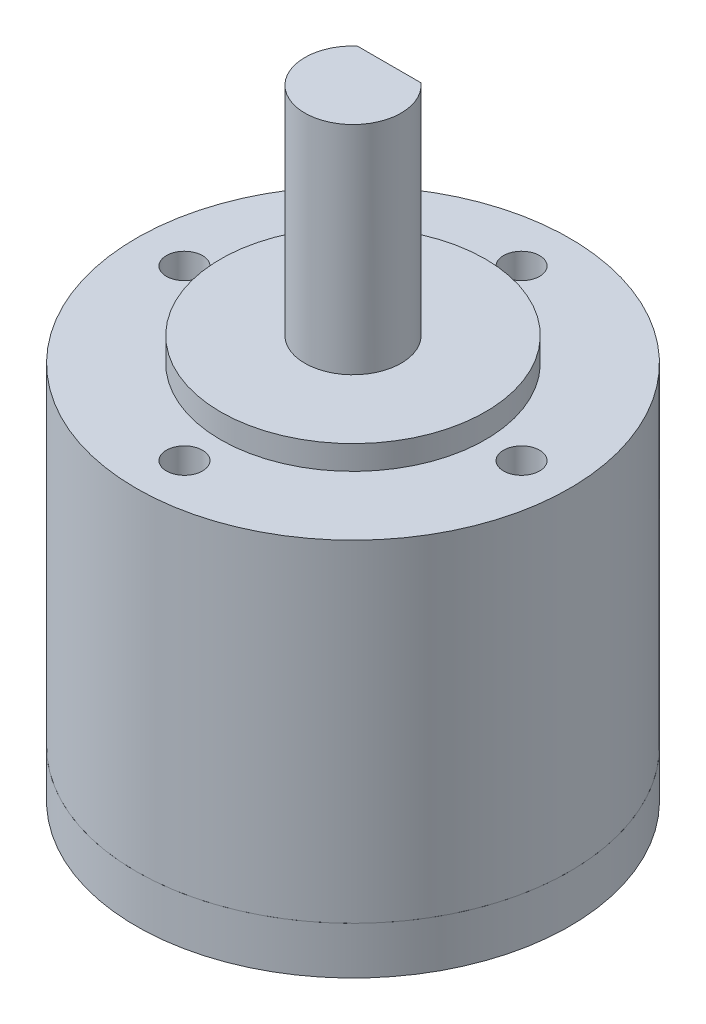
SolidWorks part; units mm, degrees
ref_plane "Front Plane" through (0, 0, 0) normal (0, 0, 1) x (1, 0, 0)
ref_plane "Top Plane" through (0, 0, 0) normal (0, 1, 0) x (1, 0, 0)
ref_plane "Right Plane" through (0, 0, 0) normal (1, 0, 0) x (0, 0, -1)
sketch "Sketch1" plane through (0, 0, 0) normal (0, 1, 0) x (1, 0, 0)
  circle A0 centre (0, 0) radius 18
  dimension "D1" = 36
extrude "Boss-Extrude1" add sketch "Sketch1" along normal mid plane 27.559
sketch "Sketch2" plane through (0, 13.7795, 0) normal (0, 1, 0) x (1, 0, 0)
  circle A0 centre (0, 0) radius 11
  dimension "D1" = 22
extrude "Boss-Extrude2" add sketch "Sketch2" along normal blind 2
sketch "Sketch3" plane through (0, 15.7795, 0) normal (0, 1, 0) x (1, 0, 0)
  circle A0 centre (0, 0) radius 4
  dimension "D1" = 8
extrude "Boss-Extrude4" add sketch "Sketch3" along normal blind 18
sketch "Sketch4" plane through (0, 33.7795, 0) normal (0, 1, 0) x (1, 0, 0)
  line L0 (-2.6458, 3) -> (2.6458, 3)
  line L1 (0, -4) -> (0, 3) construction
  arc A0 (0, -4) -> (2.6458, 3) centre (0, 0) ccw construction
  circle A1 centre (0, 0) radius 4
  arc A2 (2.6458, 3) -> (-2.6458, 3) centre (0, 0) ccw
  arc A3 (-2.6458, 3) -> (0, -4) centre (0, 0) ccw construction
  dimension "D2" = 7
  dimension "D1" = 0
extrude "Cut-Extrude1" cut sketch "Sketch4" against normal blind 15
sketch "Sketch5" plane through (0, 13.7795, 0) normal (0, 1, 0) x (1, 0, 0)
  circle A0 centre (0, 0) radius 14 construction
  circle A1 centre (0, 14) radius 1.5
  circle A2 centre (-14, 0) radius 1.5
  circle A3 centre (0, -14) radius 1.5
  circle A4 centre (14, 0) radius 1.5
  dimension "D1" = 28
  dimension "D2" = 3
extrude "Cut-Extrude2" cut sketch "Sketch5" against normal through all
sketch "Sketch6" plane through (0, -13.7795, 0) normal (0, -1, 0) x (1, 0, 0)
  circle A0 centre (0, 0) radius 11.178
  dimension "D1" = 22.356
extrude "Cut-Extrude3" cut sketch "Sketch6" against normal blind 20
sketch "Sketch7" plane through (0, -13.7795, 0) normal (0, -1, 0) x (1, 0, 0)
  circle A1 centre (0, 0) radius 18
  circle A2 centre (0, 0) radius 18
  dimension "D1" = 0
extrude "Boss-Extrude5" add sketch "Sketch7" along normal blind 3.937 separate body
sketch "Sketch8" plane through (0, -13.7795, 0) normal (0, 1, 0) x (1, 0, 0)
  circle A0 centre (0, 0) radius 10.9855
  point P2 (0, 0)
  dimension "D1" = 21.971
extrude "Boss-Extrude6" add sketch "Sketch8" along normal blind 2.413
sketch "Sketch9" plane through (0, -13.7795, 0) normal (0, 1, 0) x (1, 0, 0)
  circle A0 centre (0, 14) radius 1.265
  circle A1 centre (14, 0) radius 1.265
  circle A2 centre (0, -14) radius 1.265
  circle A3 centre (-14, 0) radius 1.265
  dimension "D1" = 2.53
extrude "Cut-Extrude4" cut sketch "Sketch9" against normal through all
sketch "Sketch10" plane through (0, -11.3665, 0) normal (0, 1, 0) x (1, 0, 0)
  circle A0 centre (0, 0) radius 4
  dimension "D1" = 8
extrude "Cut-Extrude5" cut sketch "Sketch10" against normal through all
sketch "Sketch11" plane through (0, -11.3665, 0) normal (0, 1, 0) x (1, 0, 0)
  circle A0 centre (0, 0) radius 4.75
  dimension "D1" = 9.5
extrude "Cut-Extrude6" cut sketch "Sketch11" against normal blind 0.6
